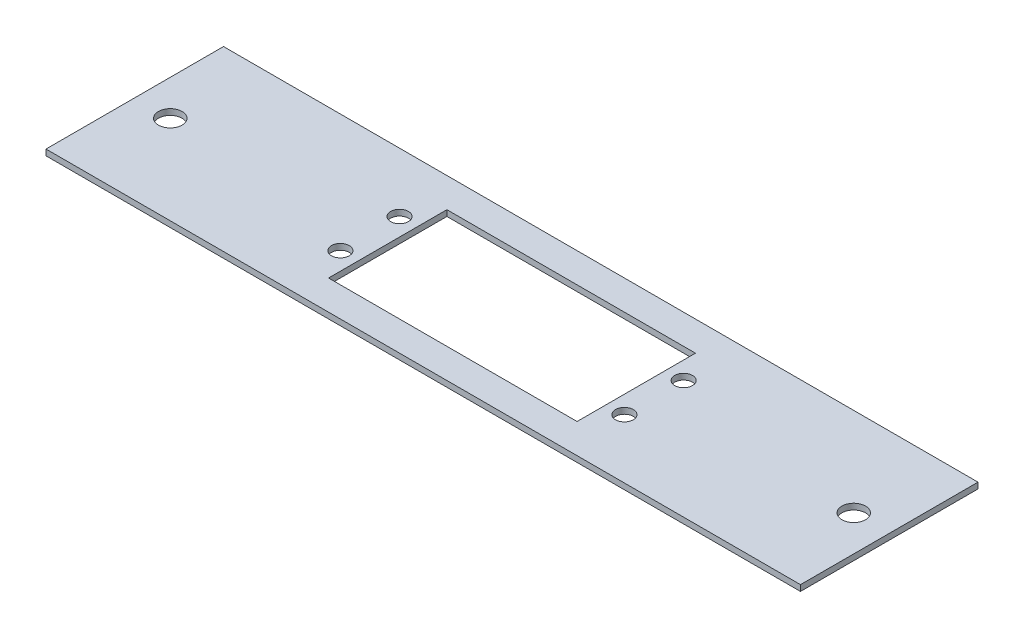
SolidWorks part; units mm, degrees
material "Balsa"
ref_plane "Front Plane" through (0, 0, 0) normal (0, 0, 1) x (1, 0, 0)
ref_plane "Top Plane" through (0, 0, 0) normal (0, 1, 0) x (1, 0, 0)
ref_plane "Right Plane" through (0, 0, 0) normal (1, 0, 0) x (0, 0, -1)
sketch "Sketch1" plane through (0, 0, 0) normal (0, 1, 0) x (1, 0, 0)
  line L0 (-21, 10) -> (-27.75, 10) construction
  line L1 (-21, -10) -> (21, -10)
  line L2 (-21, -10) -> (-21, 10)
  line L3 (-21, 10) -> (21, 10)
  line L4 (21, -10) -> (21, 10)
  line L5 (-21, -10) -> (21, 10) construction
  line L6 (-21, 10) -> (21, -10) construction
  line L7 (-27.75, 10) -> (-27.75, -10) construction
  line L8 (-27.75, -10) -> (-21, -10) construction
  line L9 (0, 10) -> (0, -10) construction
  line L10 (27.75, -10) -> (21, -10) construction
  line L11 (27.75, 10) -> (27.75, -10) construction
  line L12 (21, 10) -> (27.75, 10) construction
  line L13 (-53.9162, 0) -> (53.9162, 0) construction
  line L14 (0, 15) -> (0, -15) construction
  line L15 (-63.75, 15) -> (63.75, 15)
  line L16 (-63.75, 15) -> (-63.75, -15)
  line L17 (-63.75, -15) -> (63.75, -15)
  line L18 (63.75, 15) -> (63.75, -15)
  line L19 (-63.75, 0) -> (63.75, 0) construction
  circle A0 centre (-57.75, 0) radius 2
  circle A1 centre (57.75, 0) radius 2
  point P0 (0, 0)
  point P14 (0, 0)
  point P27 (0, 0)
  dimension "D4" = 4
  dimension "D1" = 20
  dimension "D2" = 42
  dimension "D3" = 55.5
  dimension "D5" = 30
  dimension "D6" = 30
  dimension "D7" = 6
extrude "Boss-Extrude1" add sketch "Sketch1" along normal blind 1
sketch "Sketch2" plane through (0, 1, 0) normal (0, 1, 0) x (1, 0, 0)
  line L0 (0, 15) -> (0, -15) construction
  line L1 (63.75, 15) -> (-63.75, 15) construction
  line L2 (-63.75, -15) -> (63.75, -15) construction
  line L3 (-63.75, 0) -> (63.75, 0) construction
  line L4 (-63.75, 15) -> (-63.75, -15) construction
  line L5 (63.75, -15) -> (63.75, 15) construction
  line L6 (-24, 15) -> (-24, -15) construction
  line L7 (24, 15) -> (24, -15) construction
  circle A0 centre (-24, 5) radius 1.5
  circle A1 centre (-24, -5) radius 1.5
  circle A2 centre (24, -5) radius 1.5
  circle A3 centre (24, 5) radius 1.5
  dimension "D1" = 3
  dimension "D3" = 48
  dimension "D2" = 10
extrude "Cut-Extrude1" cut sketch "Sketch2" against normal through all
